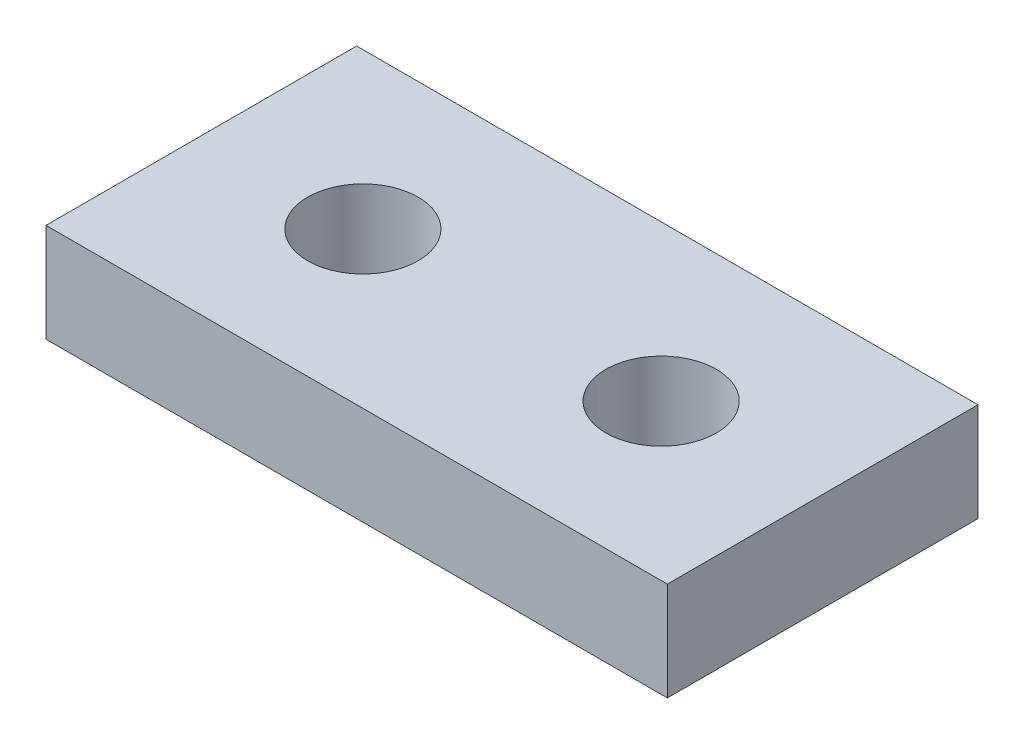
SolidWorks part; units mm, degrees
material "6061-T6 (SS)"
ref_plane "Front" through (0, 0, 0) normal (0, 0, 1) x (1, 0, 0)
ref_plane "Top" through (0, 0, 0) normal (0, 1, 0) x (1, 0, 0)
ref_plane "Right" through (0, 0, 0) normal (1, 0, 0) x (0, 0, -1)
sketch "Sketch1" plane through (0, 0, 0) normal (0, 1, 0) x (1, 0, 0)
  line L1 (-5, 2.5) -> (5, 2.5)
  line L2 (-5, 2.5) -> (-5, -2.5)
  line L3 (-5, -2.5) -> (5, -2.5)
  line L4 (5, 2.5) -> (5, -2.5)
  line L5 (-5, 2.5) -> (5, -2.5) construction
  line L6 (-5, -2.5) -> (5, 2.5) construction
  point P0 (0, 0)
  dimension "D1" = 10
  dimension "D2" = 5
extrude "Boss-Extrude1" add sketch "Sketch1" along normal blind 1.5875
sketch "Sketch2" plane through (0, 1.5875, 0) normal (0, 1, 0) x (1, 0, 0)
  line L0 (-2.4, 0) -> (2.4, 0) construction
  point P3 (0, 0)
  point P5 (2.4, 0)
  point P6 (-2.4, 0)
  dimension "D1" = 4.8
hole_wizard "#2-56 Tapped Hole1" positions "Sketch3" profile "Sketch4" tap size "#2-56" standard "ANSI Inch"
sketch "Sketch3" plane through (0, 1.5875, 0) normal (0, 1, 0) x (1, 0, 0)
  point P0 (-2.4, 0)
  point P3 (2.4, 0)
sketch "Sketch4" plane through (-2.4, 1.5875, 0) normal (1, 0, 0) x (0, 0, 1)
  line L0 (0, 0) -> (0, 6.2642)
  line L1 (0, 6.2642) -> (0.889, 5.73)
  line L2 (0.889, 5.73) -> (0.889, 0)
  line L5 (0.889, 0) -> (0, 0)
  line L10 (0, 6.2642) -> (-0.889, 5.73) construction
  line L11 (0, -6.35) -> (0, 107.95) construction
  dimension "Tap Drill Dia." = 1.778
  dimension "Tap Drill Depth" = 5.73
  dimension "Drill Angle" = 118
cosmetic thread "Hole Thread1"
cosmetic thread "Hole Thread2"
